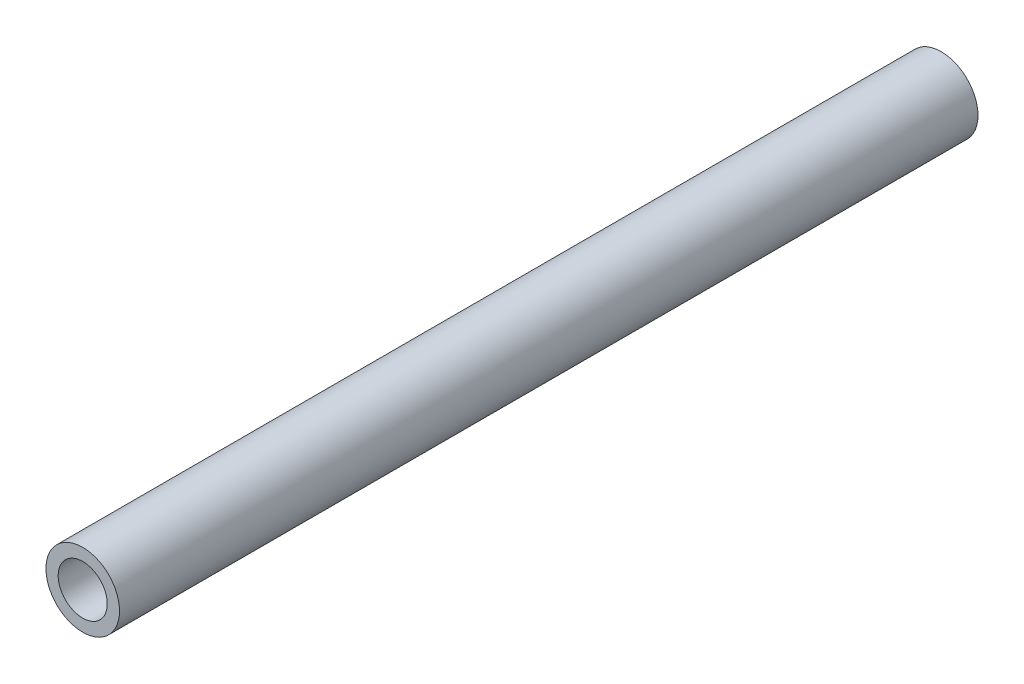
SolidWorks part; units mm, degrees
ref_plane "Front Plane" through (0, 0, 0) normal (0, 0, 1) x (1, 0, 0)
ref_plane "Top Plane" through (0, 0, 0) normal (0, 1, 0) x (1, 0, 0)
ref_plane "Right Plane" through (0, 0, 0) normal (1, 0, 0) x (0, 0, -1)
sketch "Sketch1" plane through (0, 0, 0) normal (0, 0, 1) x (1, 0, 0)
  circle A0 centre (0, 0) radius 3
  circle A1 centre (0, 0) radius 2
  dimension "D1" = 6
  dimension "D2" = 4
extrude "Boss-Extrude1" add sketch "Sketch1" along normal blind 70
